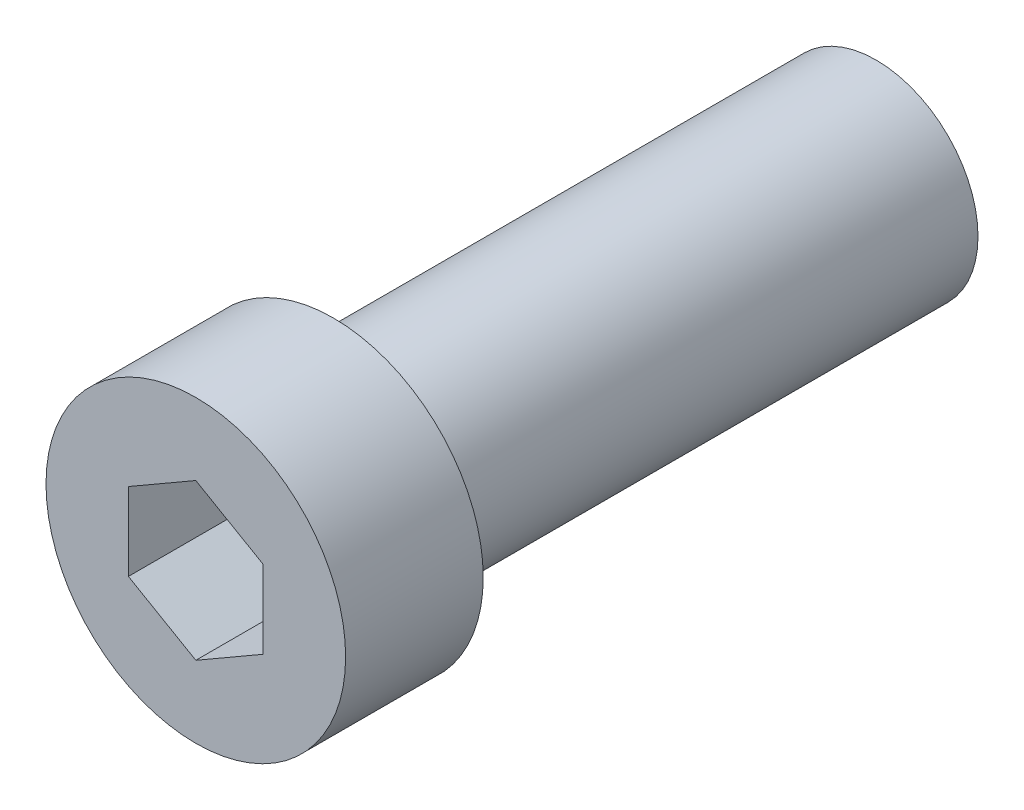
SolidWorks part; units mm, degrees
ref_plane "前视基准面" through (0, 0, 0) normal (0, 0, 1) x (1, 0, 0)
ref_plane "上视基准面" through (0, 0, 0) normal (0, 1, 0) x (1, 0, 0)
ref_plane "右视基准面" through (0, 0, 0) normal (1, 0, 0) x (0, 0, -1)
ref_plane "基准面1" through (0, 0, 0) normal (0, -1, 0) x (1, 0, 0)
sketch "草图1" plane through (0, 0, 0) normal (0, -1, 0) x (1, 0, 0)
  line L0 (2.208, 2.028) -> (0, 2.028)
  line L1 (0, 2.028) -> (0, 0)
  line L2 (0, 0) -> (2.208, 0)
  line L3 (2.208, 0) -> (2.208, 2.028)
  line L4 (0, 2.028) -> (0, 0) construction
revolve "旋转1" add sketch "草图1" angle 360 about L4
sketch "草图2" plane through (0, 0, 0) normal (0, 0, -1) x (-1, 0, 0)
  circle A0 centre (0, 0) radius 1.5
extrude "凸台-拉伸1" add sketch "草图2" along normal blind 8
sketch "草图3" plane through (0, 0, 2.028) normal (0, 0, 1) x (1, 0, 0)
  line L0 (0.9936, -0.5737) -> (0.9936, 0.5737)
  line L1 (0.9936, 0.5737) -> (0, 1.1473)
  line L2 (0, 1.1473) -> (-0.9936, 0.5737)
  line L3 (-0.9936, 0.5737) -> (-0.9936, -0.5737)
  line L4 (-0.9936, -0.5737) -> (0, -1.1473)
  line L5 (0, -1.1473) -> (0.9936, -0.5737)
extrude "切除-拉伸1" cut sketch "草图3" against normal blind 1.872
